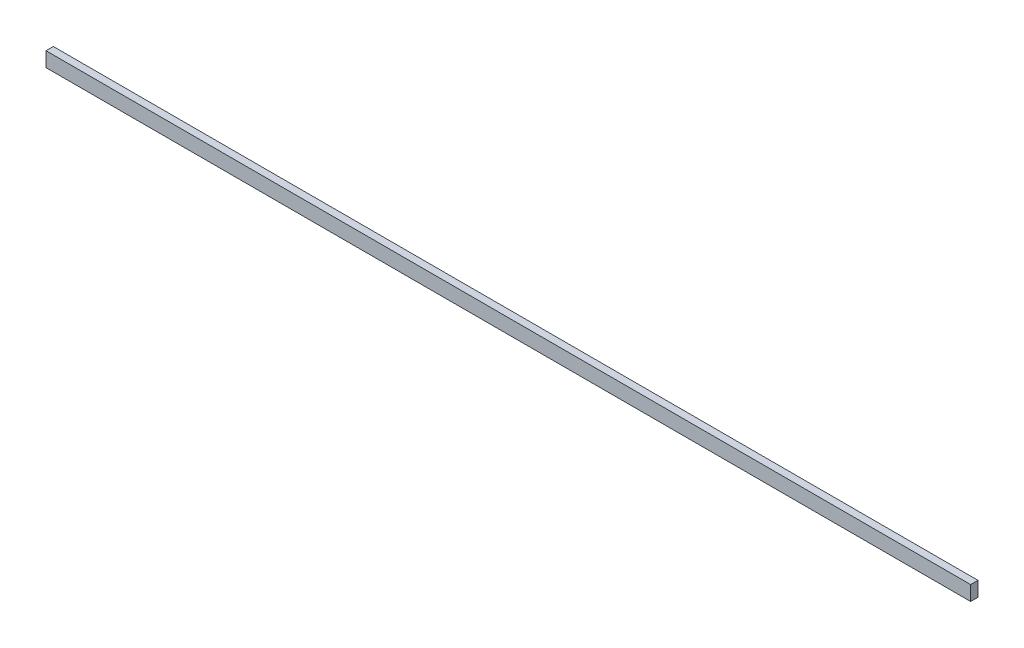
SolidWorks part; units mm, degrees
ref_plane "Front Plane" through (0, 0, 0) normal (0, 0, 1) x (1, 0, 0)
ref_plane "Top Plane" through (0, 0, 0) normal (0, 1, 0) x (1, 0, 0)
ref_plane "Right Plane" through (0, 0, 0) normal (1, 0, 0) x (0, 0, -1)
sketch "Sketch1" plane through (0, 0, 0) normal (0, 1, 0) x (1, 0, 0)
  line L1 (0, 0) -> (630, 0)
  line L2 (0, 0) -> (0, -5)
  line L3 (0, -5) -> (630, -5)
  line L4 (630, 0) -> (630, -5)
  dimension "D1" = 630
  dimension "D2" = 5
extrude "Boss-Extrude1" add sketch "Sketch1" along normal blind 10
